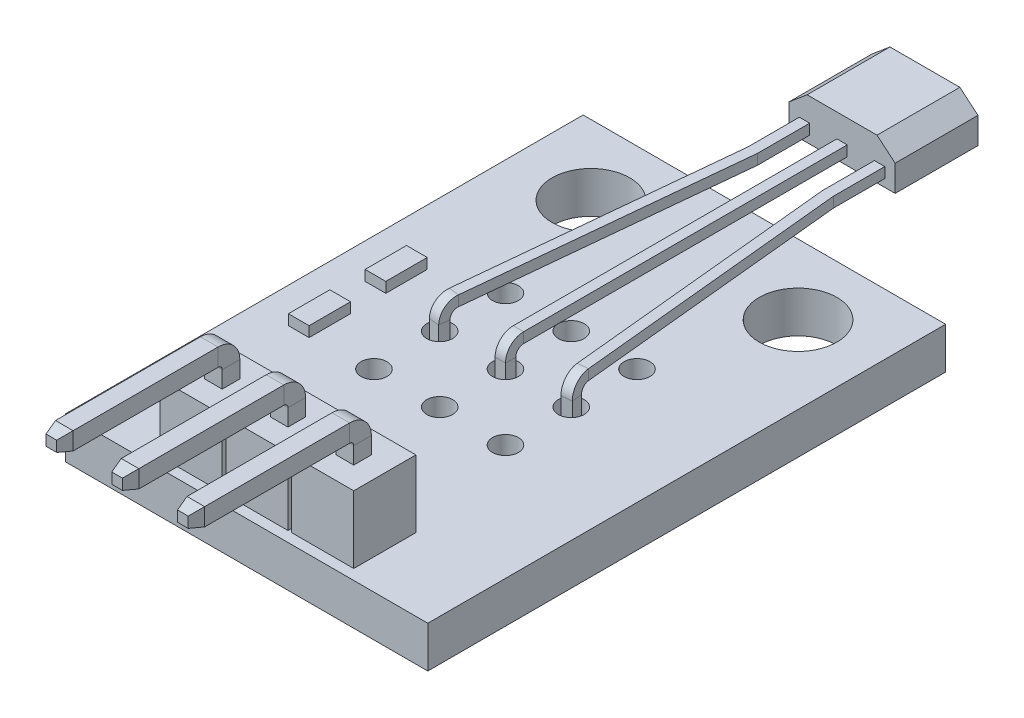
SolidWorks part; units mm, degrees
material "6063-T6"
ref_plane "Front Plane" through (0, 0, 0) normal (0, 0, 1) x (1, 0, 0)
ref_plane "Top Plane" through (0, 0, 0) normal (0, 1, 0) x (1, 0, 0)
ref_plane "Right Plane" through (0, 0, 0) normal (1, 0, 0) x (0, 0, -1)
sketch "Sketch1" plane through (0, 0, 0) normal (0, 1, 0) x (1, 0, 0)
  line L0 (-7, 0) -> (7, 0) construction
  line L1 (-7, 10) -> (7, 10)
  line L2 (-7, 10) -> (-7, -10)
  line L3 (-7, -10) -> (7, -10)
  line L4 (7, 10) -> (7, -10)
  dimension "D1" = 20
  dimension "D2" = 14
extrude "Boss-Extrude1" add sketch "Sketch1" along normal blind 1.6
sketch "Sketch2" plane through (0, 1.6, 0) normal (0, 1, 0) x (1, 0, 0)
  line L0 (-1.2, -7.2) -> (1.2, -7.2)
  line L1 (-3.74, -7.2) -> (-1.34, -7.2)
  line L2 (-3.74, -7.2) -> (-3.74, -9.6)
  line L3 (-3.74, -9.6) -> (-1.34, -9.6)
  line L4 (-1.34, -7.2) -> (-1.34, -9.6)
  line L5 (-1.2, -7.2) -> (-1.2, -9.6)
  line L6 (-1.2, -9.6) -> (1.2, -9.6)
  line L7 (1.2, -7.2) -> (1.2, -9.6)
  line L8 (1.34, -7.2) -> (3.74, -7.2)
  line L9 (1.34, -7.2) -> (1.34, -9.6)
  line L10 (1.34, -9.6) -> (3.74, -9.6)
  line L11 (3.74, -7.2) -> (3.74, -9.6)
  line L12 (0, 0) -> (0, -7.2) construction
  line L13 (7, 10) -> (-7, 10) construction
  dimension "D1" = 2.4
  dimension "D3" = 2.54
  dimension "D4" = 19.6
  dimension "D2" = 3
extrude "Boss-Extrude2" add sketch "Sketch2" along normal blind 2.6
ref_plane "Plane1" through (0, 0, 15) normal (0, 0, -1) x (-1, 0, 0)
sketch "Sketch3" plane through (0, 0, 0) normal (1, 0, 0) x (0, 0, -1)
  line L0 (-15, 5.35) -> (-8.9, 5.35)
  line L1 (-8.4, 4.85) -> (-8.4, -1)
  line L2 (10, 0) -> (-10, 0) construction
  line L3 (-7.2, 4.2) -> (-9.6, 4.2) construction
  line L4 (-15, -0.88) -> (-15, 0.88) construction
  line L5 (10, 1.6) -> (-10, 1.6) construction
  arc A0 (-8.9, 5.35) -> (-8.4, 4.85) centre (-8.9, 4.85) cw
  point P7 (-8.4, 4.2)
  dimension "D1" = 0.5
  dimension "D2" = 1
  dimension "D3" = 3.75
sketch "Sketch4" plane through (0, 0, 15) normal (0, 0, -1) x (-1, 0, 0)
  line L0 (0.34, 5.69) -> (-0.34, 5.69)
  line L1 (2.88, 5.69) -> (2.2, 5.69)
  line L2 (2.88, 5.69) -> (2.88, 5.01)
  line L3 (2.88, 5.01) -> (2.2, 5.01)
  line L4 (2.2, 5.69) -> (2.2, 5.01)
  line L5 (-0.34, 5.69) -> (-0.34, 5.01)
  line L6 (0.34, 5.01) -> (-0.34, 5.01)
  line L7 (0.34, 5.69) -> (0.34, 5.01)
  line L8 (-2.2, 5.69) -> (-2.88, 5.69)
  line L9 (-2.88, 5.69) -> (-2.88, 5.01)
  line L10 (-2.2, 5.01) -> (-2.88, 5.01)
  line L11 (-2.2, 5.69) -> (-2.2, 5.01)
  line L12 (0.34, 5.35) -> (-0.34, 5.35) construction
  line L13 (2.54, 5.01) -> (2.54, 4.2) construction
  line L14 (3.74, 4.2) -> (1.34, 4.2) construction
  dimension "D1" = 0.68
  dimension "D2" = 3
sweep "Sweep1" add profiles "Sketch4" path "Sketch3"
sketch "Sketch8" plane through (0, 1.6, 0) normal (0, 1, 0) x (1, 0, 0)
  line L0 (-2.54, -8.06) -> (-2.54, -2.54) construction
  line L1 (-2.2, -8.06) -> (-2.88, -8.06) construction
  line L2 (-2.54, -2.54) -> (-2.54, 0) construction
  line L3 (-2.54, 0) -> (0, 0) construction
  circle A0 centre (-2.54, 2.54) radius 0.5
  circle A1 centre (0, 2.54) radius 0.5
  circle A2 centre (2.54, 2.54) radius 0.5
  circle A3 centre (0, 0) radius 0.5
  circle A4 centre (2.54, 0) radius 0.5
  circle A5 centre (0, -2.54) radius 0.5
  circle A6 centre (2.54, -2.54) radius 0.5
  circle A7 centre (-2.54, 0) radius 0.5
  circle A8 centre (-2.54, -2.54) radius 0.5
  dimension "D1" = 1
  dimension "D2" = 3
  dimension "D3" = 3
extrude "Cut-Extrude2" cut sketch "Sketch8" against normal through all
chamfer "Chamfer1" distance 0.5 angle 15 24 edges at (-2.54, -1, 8.74) (-2.2, -1, 8.4) (-2.54, -1, 8.06) (-2.88, -1, 8.4) (0, -1, 8.74) (0.34, -1, 8.4) (0, -1, 8.06) (-0.34, -1, 8.4) (2.54, -1, 8.74) (2.88, -1, 8.4) (2.54, -1, 8.06) (2.2, -1, 8.4) (2.54, 5.69, 15) (2.88, 5.35, 15) (2.54, 5.01, 15) (2.2, 5.35, 15) (0, 5.69, 15) (0.34, 5.35, 15) (0, 5.01, 15) (-0.34, 5.35, 15) (-2.54, 5.69, 15) (-2.2, 5.35, 15) (-2.54, 5.01, 15) (-2.88, 5.35, 15)
sketch "Sketch5" plane through (0, 1.6, 0) normal (0, 1, 0) x (1, 0, 0)
  line L0 (-4, 7.3) -> (4, 7.3) construction
  line L1 (0, 7.3) -> (0, 0) construction
  line L2 (-7, -10) -> (7, -10) construction
  line L3 (7, 10) -> (-7, 10) construction
  circle A0 centre (-4, 7.3) radius 1.5
  circle A1 centre (4, 7.3) radius 1.5
  dimension "D1" = 3
  dimension "D2" = 5
  dimension "D3" = 11
  dimension "D4" = 15.8
  dimension "D5" = 1.2
extrude "Cut-Extrude1" cut sketch "Sketch5" against normal through all
ref_plane "Plane2" through (0, 0, -13) normal (0, 0, -1) x (-1, 0, 0)
sketch "Sketch6" plane through (0, 0, -13) normal (0, 0, -1) x (-1, 0, 0)
  line L0 (0, 2) -> (0, 0) construction
  line L1 (2.05, 3.6) -> (-2.05, 3.6)
  line L2 (2.05, 3.6) -> (2.05, 2)
  line L3 (2.05, 2) -> (-2.05, 2)
  line L4 (-2.05, 3.6) -> (-2.05, 2)
  line L5 (-7, 1.6) -> (7, 1.6) construction
  dimension "D1" = 4.1
  dimension "D2" = 1.6
  dimension "D3" = 2
extrude "Boss-Extrude3" add sketch "Sketch6" along normal blind 3.2 separate body
chamfer "Chamfer2" distance 0.7 angle 40 2 edges at (-2.05, 3.6, -14.6) (2.05, 3.6, -14.6)
sketch "Sketch7" plane through (0, 2, 0) normal (0, -1, 0) x (1, 0, 0)
  line L0 (1.45, -13) -> (1.45, -11) construction
  line L5 (2.05, -13) -> (-2.05, -13) construction
  line L6 (1.45, -11) -> (2.4382, -1.0274) construction
  line L7 (0, -13) -> (0, -1.0274) construction
  line L8 (-1.45, -13) -> (-1.45, -11) construction
  line L9 (-1.45, -11) -> (-2.4382, -1.0274) construction
  line L10 (2.4382, -1.0274) -> (-2.4382, -1.0274) construction
  line L11 (1.45, -13) -> (-1.45, -13) construction
  line L12 (1.45, -11) -> (-1.45, -11) construction
  line L13 (2.4382, -1.0274) -> (2.54, 0) construction
  line L15 (1.65, -13) -> (1.65, -11.0099)
  line L16 (1.65, -11.0099) -> (2.6372, -1.0472)
  line L17 (0.2, -13) -> (0.2, -1.0274)
  line L18 (-1.25, -13) -> (-1.25, -10.9901)
  line L19 (-1.25, -10.9901) -> (-2.2392, -1.0077)
  line L20 (1.25, -13) -> (1.25, -10.9901)
  line L21 (1.25, -10.9901) -> (2.2392, -1.0077)
  line L22 (-0.2, -13) -> (-0.2, -1.0274)
  line L23 (-1.65, -13) -> (-1.65, -11.0099)
  line L24 (-1.65, -11.0099) -> (-2.6372, -1.0472)
  line L25 (1.65, -13) -> (1.25, -13)
  line L26 (2.6372, -1.0472) -> (2.2392, -1.0077)
  line L27 (0.2, -13) -> (-0.2, -13)
  line L28 (0.2, -1.0274) -> (-0.2, -1.0274)
  line L29 (-1.25, -13) -> (-1.65, -13)
  line L30 (-2.2392, -1.0077) -> (-2.6372, -1.0472)
  line L31 (0, -13) -> (0, -1.0274) construction
  line L32 (0, -1.0274) -> (0, 0) construction
  line L33 (2.54, 0) -> (2.54, 8.06) construction
  line L34 (2.88, 8.06) -> (2.2, 8.06) construction
  line L35 (0, 0) -> (2.54, 0) construction
  dimension "D1" = 1.45
  dimension "D2" = 2
  dimension "D3" = 0.2
  dimension "D4" = 0.2
extrude "Boss-Extrude4" add sketch "Sketch7" against normal blind 0.4 from offset 0.3 offset against normal yes
sketch "Sketch9" plane through (0, 0, 0) normal (1, 0, 0) x (0, 0, -1)
  line L0 (0, -1) -> (0, 2)
  line L1 (0.5, 2.5) -> (1.0274, 2.5)
  line L2 (1.0274, 2.7) -> (1.0274, 2.3) construction
  line L3 (-8.606, -1) -> (-8.194, -1) construction
  arc A0 (0, 2) -> (0.5, 2.5) centre (0.5, 2) cw
  dimension "D1" = 0.5
sketch "Sketch10" plane through (0, 0, -1.0274) normal (0, 0, 1) x (1, 0, 0)
  line L4 (-0.2, 2.3) -> (0.2, 2.3)
  line L5 (0.2, 2.3) -> (0.2, 2.7)
  line L6 (0.2, 2.7) -> (-0.2, 2.7)
  line L7 (-0.2, 2.7) -> (-0.2, 2.3)
  line L8 (-0.2, 2.3) -> (0.2, 2.3)
  line L9 (0.2, 2.3) -> (0.2, 2.7)
  line L10 (0.2, 2.7) -> (-0.2, 2.7)
  line L11 (-0.2, 2.7) -> (-0.2, 2.3)
  dimension "D1" = 0
sweep "Sweep2" add profiles "Sketch10" path "Sketch9"
sketch "Sketch11" plane through (-2.7143, 0, -0.269) normal (-0.9951, 0, -0.0986) x (-0.0986, 0, 0.9951)
  line L0 (-0.782, 2.5) -> (-0.2495, 2.5)
  line L1 (-0.782, 2.7) -> (-0.782, 2.3) construction
  line L2 (0.2505, 2) -> (0.2505, -1)
  line L3 (0.7505, 1.6) -> (-0.2495, 1.6) construction
  line L4 (-0.2187, -1) -> (0.1793, -1) construction
  arc A0 (-0.2495, 2.5) -> (0.2505, 2) centre (-0.2495, 2) cw
  point P7 (0.2505, 1.6)
  dimension "D1" = 0.5
sketch "Sketch12" plane through (0.0771, 0, -0.7782) normal (-0.0986, 0, 0.9951) x (0.9951, 0, 0.0986)
  line L4 (-2.7276, 2.3) -> (-2.3276, 2.3)
  line L5 (-2.3276, 2.3) -> (-2.3276, 2.7)
  line L6 (-2.3276, 2.7) -> (-2.7276, 2.7)
  line L7 (-2.7276, 2.7) -> (-2.7276, 2.3)
  line L8 (-2.7276, 2.3) -> (-2.3276, 2.3)
  line L9 (-2.3276, 2.3) -> (-2.3276, 2.7)
  line L10 (-2.3276, 2.7) -> (-2.7276, 2.7)
  line L11 (-2.7276, 2.7) -> (-2.7276, 2.3)
  dimension "D1" = 0
sweep "Sweep3" add profiles "Sketch12" path "Sketch11"
mirror "Mirror1" about plane through (0, 0, 0) normal (1, 0, 0) of "Sweep3"
sketch "Sketch13" plane through (0, 1.6, 0) normal (0, 1, 0) x (1, 0, 0)
  line L1 (-5.6451, 1.8227) -> (-4.8451, 1.8227)
  line L2 (-5.6451, 1.8227) -> (-5.6451, 0.2227)
  line L3 (-5.6451, 0.2227) -> (-4.8451, 0.2227)
  line L4 (-4.8451, 1.8227) -> (-4.8451, 0.2227)
  line L5 (-5.6451, -1.1401) -> (-4.8451, -1.1401)
  line L6 (-5.6451, -1.1401) -> (-5.6451, -2.7401)
  line L7 (-5.6451, -2.7401) -> (-4.8451, -2.7401)
  line L8 (-4.8451, -1.1401) -> (-4.8451, -2.7401)
  dimension "D1" = 1.6
  dimension "D2" = 0.8
extrude "Boss-Extrude5" add sketch "Sketch13" along normal blind 0.4
